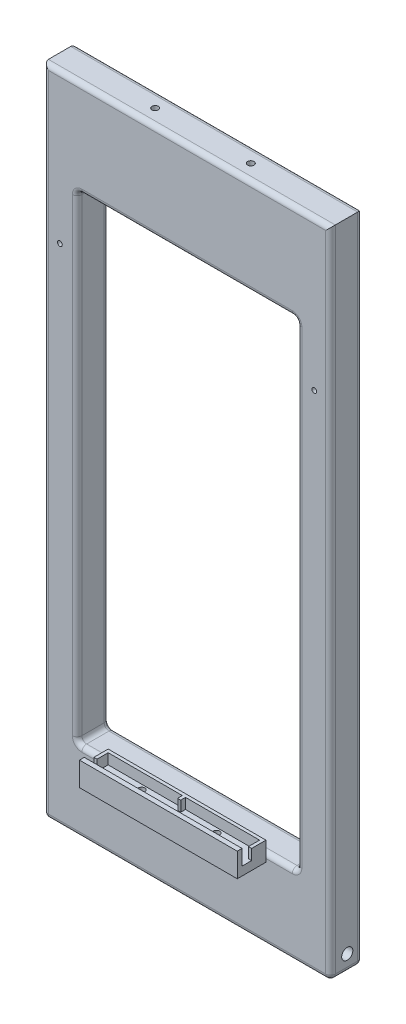
SolidWorks part; units mm, degrees
ref_plane "Plan de face" through (0, 0, 0) normal (0, 0, 1) x (1, 0, 0)
ref_plane "Plan de dessus" through (0, 0, 0) normal (0, 1, 0) x (1, 0, 0)
ref_plane "Plan de droite" through (0, 0, 0) normal (1, 0, 0) x (0, 0, -1)
sketch "Esquisse1" plane through (0, 0, 0) normal (0, 0, 1) x (1, 0, 0)
  line L0 (0, 205) -> (0, -205) construction
  line L1 (-90, 205) -> (90, 205)
  line L2 (-90, 205) -> (-90, -205)
  line L3 (-90, -205) -> (90, -205)
  line L4 (90, 205) -> (90, -205)
  line L5 (-90, 0) -> (265.1351, 0) construction
  line L11 (-69, 145) -> (69, 145)
  line L12 (-69, 145) -> (-69, -155)
  line L13 (-69, -155) -> (69, -155)
  line L14 (69, 145) -> (69, -155)
  dimension "D1" = 410
  dimension "D2" = 180
  dimension "D4" = 50
  dimension "D3" = 60
  dimension "D5" = 21
extrude "Boss.-Extru.1" add sketch "Esquisse1" along normal blind 20
fillet "Congé1" radius 3 22 edges at (0, 145, 0) (-69, -5, 0) (69, -5, 0) (-90, -205, 10) (90, -205, 10) (0, -205, 0) (69, -5, 20) (0, 145, 20) (-69, -5, 20) (0, -155, 20) (0, 205, 20) (90, 0, 20) (0, -205, 20) (-90, 0, 20) (0, -155, 0) (0, 205, 0) (-69, -155, 10) (69, -155, 10) (69, 145, 10) (-69, 145, 10) (90, 0, 0) (-90, 0, 0)
sketch "Esquisse2" plane through (0, 145, 0) normal (0, -1, 0) x (1, 0, 0)
  line L0 (0, 0) -> (0, 35.1833) construction
  line L1 (-66, 10) -> (38.6684, 10) construction
  line L2 (-66, 17) -> (-66, 3) construction
  circle A0 centre (-30, 10) radius 2
  circle A1 centre (30, 10) radius 2
  dimension "D2" = 4
  dimension "D1" = 60
extrude "Enlèv. mat.-Extru.1" cut sketch "Esquisse2" against normal through all
sketch "Esquisse3" plane through (0, 0, 20) normal (0, 0, 1) x (1, 0, 0)
  line L0 (0, 145) -> (0, -111.4932) construction
  line L1 (66, 145) -> (-66, 145) construction
  circle A0 centre (-79.7986, 111.4932) radius 1.5
  circle A1 centre (79.7986, 111.4932) radius 1.5
  dimension "D1" = 3
extrude "Enlèv. mat.-Extru.2" cut sketch "Esquisse3" against normal through all
sketch "Esquisse4" plane through (-90, 0, 0) normal (-1, 0, 0) x (0, 0, 1)
  circle A0 centre (9.5071, -194.7549) radius 3.5
  dimension "D1" = 7
extrude "Enlèv. mat.-Extru.3" cut sketch "Esquisse4" against normal through all
sketch "Esquisse5" plane through (0, 0, 20) normal (0, 0, 1) x (1, 0, 0)
  line L0 (0, 0) -> (0, -217.6179) construction
  line L1 (-49.5, -160) -> (49.5, -160)
  line L2 (-49.5, -160) -> (-49.5, -148)
  line L3 (-49.5, -148) -> (49.5, -148)
  line L4 (49.5, -160) -> (49.5, -148)
  line L5 (66, -158) -> (-66, -158) construction
  line L6 (66, -158) -> (-66, -158) construction
  line L7 (-66, -155) -> (66, -155) construction
  dimension "D1" = 99
  dimension "D2" = 12
  dimension "D3" = 7
extrude "Boss.-Extru.2" add sketch "Esquisse5" along normal blind 18
sketch "Esquisse7" plane through (0, 0, 0) normal (0, 0, -1) x (-1, 0, 0)
  line L0 (0, 202) -> (0, 300.5496) construction
  line L1 (87, 202) -> (-87, 202) construction
sketch "Esquisse8" plane through (0, 0, 20) normal (0, 0, 1) x (1, 0, 0)
  line L0 (0, 202) -> (0, 318.6563) construction
  line L1 (0, 268.0954) -> (0, 617.8714) construction
sketch "Esquisse12" plane through (-49.5, 0, 0) normal (-1, 0, 0) x (0, 0, 1)
  line L1 (38, -148) -> (35, -148)
  line L2 (38, -148) -> (38, -145)
  line L3 (38, -145) -> (35, -145)
  line L4 (35, -148) -> (35, -145)
  dimension "D1" = 3
  dimension "D2" = 3
extrude "Boss.-Extru.5" add sketch "Esquisse12" against normal up to surface (99 mm away) up to face at (49.5, -154.8, 27.2)
sketch "Esquisse13" plane through (-49.5, 0, 0) normal (-1, 0, 0) x (0, 0, 1)
  line L0 (35, -148) -> (20, -148) construction
  line L1 (29, -148) -> (35, -148)
  line L2 (29, -148) -> (29, -154.6096)
  line L3 (29, -154.6096) -> (35, -154.6096)
  line L4 (35, -148) -> (35, -154.6096)
  line L5 (20, 202) -> (20, -202) construction
  dimension "D1" = 9
  dimension "D2" = 6
extrude "Enlèv. mat.-Extru.5" cut sketch "Esquisse13" against normal up to surface (99 mm away) contours L2 L1 L4 L3 up to face at (49.5, -152, 29.4286)
sketch "Esquisse14" plane through (0, -148, 0) normal (0, 1, 0) x (1, 0, 0)
  line L0 (49.5, -29) -> (49.5, -20) construction
  line L1 (49.5, -20) -> (-49.5, -20) construction
  line L2 (-49.5, -29) -> (-49.5, -20) construction
  line L3 (49.5, -29) -> (49.5, -20) construction
  line L4 (49.5, -20) -> (-49.5, -20) construction
  line L5 (-49.5, -29) -> (-49.5, -20) construction
  line L6 (-47.5, -29) -> (-47.5, -22)
  line L7 (47.5, -22) -> (1, -22)
  line L8 (47.5, -29) -> (47.5, -22)
  line L9 (-47.5, -29) -> (47.5, -29)
  line L10 (0, -22) -> (0, -43.1049) construction
  line L11 (-1, -22) -> (-47.5, -22)
  line L13 (-1, -22) -> (-1, -24.7)
  line L14 (-0.7, -25) -> (0.7, -25)
  line L15 (1, -22) -> (1, -24.7)
  line L17 (47.5, -22) -> (-47.5, -22) construction
  arc A0 (0.7, -25) -> (1, -24.7) centre (0.7, -24.7) ccw
  arc A1 (-1, -24.7) -> (-0.7, -25) centre (-0.7, -24.7) ccw
  point P17 (1, -25)
  point P20 (-1, -25)
  dimension "D4" = 0.3
  dimension "D2" = 2
  dimension "D3" = 3
  dimension "D1" = 2
extrude "Enlèv. mat.-Extru.6" cut sketch "Esquisse14" against normal up to surface (6.6096 mm away) contours L9 L8 L7 L15 A0 L14 A1 L13 L11 L6 up to face at (0, -154.6096, 32)
sketch "Esquisse15" plane through (0, -154.6096, 0) normal (0, 1, 0) x (1, 0, 0)
  line L0 (0, 0) -> (0, -66.1622) construction
  line L2 (47.5, -22) -> (1, -22) construction
  circle A0 centre (-23.5, -25) radius 2
  circle A1 centre (23.5, -25) radius 2
  point P7 (0, 0)
  point P8 (0, 0)
  point P9 (-23.0635, -22)
  dimension "D1" = 4
  dimension "D2" = 3
extrude "Enlèv. mat.-Extru.7" cut sketch "Esquisse15" against normal through all contours A0 | A1
